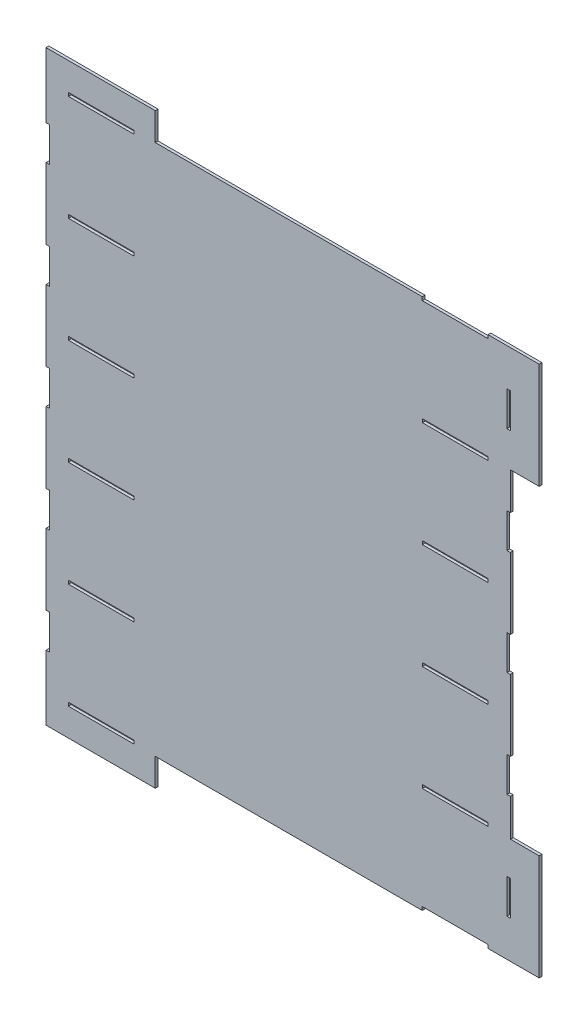
SolidWorks part; units mm, degrees
material "6061-T6 (SS)"
ref_plane "X-Y Datum" through (0, 0, 0) normal (0, 0, 1) x (1, 0, 0)
ref_plane "X-Z Datum" through (0, 0, 0) normal (0, 1, 0) x (1, 0, 0)
ref_plane "Y-Z Datum" through (0, 0, 0) normal (1, 0, 0) x (0, 0, -1)
sketch "Sketch2" plane through (0, 0, 0) normal (0, 0, 1) x (1, 0, 0)
  line L111 (-213.36, -263.2075) -> (-213.36, -269.6845)
  line L123 (-213.36, 244.2845) -> (-213.36, -244.2845)
  line L125 (213.36, 205.7205) -> (213.36, 174.8985)
  line L126 (-213.36, 244.2845) -> (213.36, -244.2845) construction
  line L127 (-213.36, -244.2845) -> (213.36, 244.2845) construction
  line L128 (132.334, -244.2845) -> (192.786, -244.2845)
  line L129 (132.334, -244.2845) -> (132.334, -241.1095)
  line L130 (132.334, -241.1095) -> (192.786, -241.1095)
  line L131 (192.786, -244.2845) -> (192.786, -241.1095)
  line L132 (0, -43.0151) -> (0, 43.0151) construction
  line L136 (55.1739, 0) -> (-55.1739, 0) construction
  line L137 (-213.36, -44.577) -> (213.36, -44.577) construction
  line L138 (-213.36, -134.239) -> (213.36, -134.239) construction
  line L142 (-213.36, 0) -> (213.36, 0) construction
  line L144 (213.36, -194.945) -> (213.36, -163.195)
  line L147 (-217.17, 100.6475) -> (209.55, 100.6475) construction
  line L148 (-217.17, 190.3095) -> (209.55, 190.3095) construction
  line L149 (213.36, 116.0585) -> (210.185, 116.0585) construction
  line L150 (-213.36, -89.662) -> (213.36, -89.662) construction
  line L151 (-213.36, -179.07) -> (213.36, -179.07) construction
  line L152 (213.36, -194.945) -> (210.185, -194.945) construction
  line L154 (210.185, -194.945) -> (210.185, -163.195) construction
  line L155 (-213.36, -194.945) -> (-210.185, -194.945) construction
  line L156 (-210.185, -194.945) -> (-210.185, -163.195) construction
  line L157 (-210.185, -163.195) -> (-213.36, -163.195) construction
  line L158 (-210.185, -73.533) -> (-213.36, -73.533) construction
  line L159 (-210.185, -105.283) -> (-210.185, -73.533) construction
  line L160 (-213.36, -105.283) -> (-210.185, -105.283) construction
  line L161 (210.185, 116.0585) -> (210.185, 85.2365) construction
  line L162 (210.185, 85.2365) -> (213.36, 85.2365) construction
  line L163 (213.36, 26.3965) -> (210.185, 26.3965) construction
  line L164 (-210.185, 16.129) -> (-213.36, 16.129) construction
  line L165 (-210.185, -15.621) -> (-210.185, 16.129) construction
  line L166 (-213.36, -15.621) -> (-210.185, -15.621) construction
  line L167 (210.185, 26.3965) -> (210.185, -4.4255) construction
  line L168 (210.185, -4.4255) -> (213.36, -4.4255) construction
  line L169 (213.36, -63.2655) -> (210.185, -63.2655) construction
  line L170 (-210.185, 105.791) -> (-213.36, 105.791) construction
  line L171 (-210.185, 74.041) -> (-210.185, 105.791) construction
  line L172 (-213.36, 74.041) -> (-210.185, 74.041) construction
  line L173 (210.185, -63.2655) -> (210.185, -94.0875) construction
  line L174 (210.185, -94.0875) -> (213.36, -94.0875) construction
  line L175 (213.36, 244.2845) -> (239.8083, 244.2845)
  line L176 (-210.185, 195.453) -> (-213.36, 195.453) construction
  line L177 (-210.185, 163.703) -> (-210.185, 195.453) construction
  line L178 (-213.36, 163.703) -> (-210.185, 163.703) construction
  line L179 (213.36, 205.7205) -> (210.185, 205.7205) construction
  line L180 (210.185, 205.7205) -> (210.185, 174.8985) construction
  line L181 (210.185, 174.8985) -> (213.36, 174.8985) construction
  line L183 (-213.36, 244.2845) -> (-213.36, 269.6845)
  line L184 (-213.36, 269.6845) -> (-113.03, 269.6845)
  line L185 (-113.03, 269.6845) -> (-113.03, 244.2845)
  line L186 (-113.03, 244.2845) -> (213.36, 244.2845)
  line L189 (-213.36, -244.2845) -> (-213.36, -263.2075)
  line L190 (-213.36, -269.6845) -> (-113.03, -269.6845)
  line L191 (213.36, -244.2845) -> (239.8083, -244.2845)
  line L192 (239.8083, -244.2845) -> (239.8083, -147.0025)
  line L193 (239.8083, -147.0025) -> (213.36, -147.0025)
  line L194 (210.185, -163.195) -> (213.36, -163.195) construction
  line L195 (239.8083, 244.2845) -> (239.8083, 147.0025)
  line L196 (239.8083, 147.0025) -> (213.36, 147.0025)
  line L197 (213.36, 147.0025) -> (213.36, -147.0025)
  line L205 (132.334, -225.2345) -> (192.786, -225.2345) construction
  line L206 (132.334, -225.2345) -> (132.334, -228.4095) construction
  line L207 (132.334, -228.4095) -> (192.786, -228.4095) construction
  line L208 (192.786, -225.2345) -> (192.786, -228.4095) construction
  line L216 (192.786, 225.2345) -> (192.786, 228.4095) construction
  line L217 (132.334, 225.2345) -> (192.786, 225.2345) construction
  line L218 (132.334, 228.4095) -> (192.786, 228.4095) construction
  line L219 (132.334, 225.2345) -> (132.334, 228.4095) construction
  line L220 (132.334, 244.2845) -> (132.334, 241.1095)
  line L221 (192.786, 244.2845) -> (192.786, 241.1095)
  line L222 (132.334, 244.2845) -> (192.786, 244.2845)
  line L223 (132.334, 241.1095) -> (192.786, 241.1095)
  line L224 (-192.786, -244.2845) -> (-192.786, -241.1095)
  line L225 (-192.786, -225.2345) -> (-192.786, -228.4095)
  line L226 (-132.334, -225.2345) -> (-132.334, -228.4095) construction
  line L227 (-132.334, -244.2845) -> (-132.334, -241.1095)
  line L228 (-132.334, -244.2845) -> (-192.786, -244.2845)
  line L229 (-132.334, -241.1095) -> (-192.786, -241.1095)
  line L230 (-132.334, -225.2345) -> (-192.786, -225.2345) construction
  line L231 (-132.334, -228.4095) -> (-192.786, -228.4095) construction
  line L232 (-132.334, 225.2345) -> (-132.334, 228.4095) construction
  line L233 (-192.786, 225.2345) -> (-192.786, 228.4095) construction
  line L234 (-132.334, 225.2345) -> (-192.786, 225.2345) construction
  line L235 (-132.334, 228.4095) -> (-192.786, 228.4095) construction
  line L236 (-192.786, 244.2845) -> (-192.786, 241.1095)
  line L237 (-132.334, 244.2845) -> (-132.334, 241.1095)
  line L238 (-132.334, 241.1095) -> (-192.786, 241.1095)
  line L239 (192.659, -127.889) -> (192.659, -124.714) construction
  line L240 (132.334, -140.589) -> (192.659, -140.589) construction
  line L241 (132.334, -140.589) -> (132.334, -143.764) construction
  line L242 (132.334, -143.764) -> (192.659, -143.764) construction
  line L243 (192.659, -140.589) -> (192.659, -143.764) construction
  line L244 (132.334, -127.889) -> (132.334, -124.714) construction
  line L245 (132.334, -127.889) -> (192.659, -127.889) construction
  line L246 (132.334, -124.714) -> (192.659, -124.714) construction
  line L247 (132.334, -50.927) -> (192.659, -50.927) construction
  line L248 (132.334, -54.102) -> (192.659, -54.102) construction
  line L249 (132.334, -50.927) -> (132.334, -54.102) construction
  line L250 (192.659, -50.927) -> (192.659, -54.102) construction
  line L251 (192.659, -38.227) -> (192.659, -35.052) construction
  line L252 (132.334, -38.227) -> (192.659, -38.227) construction
  line L253 (132.334, -35.052) -> (192.659, -35.052) construction
  line L254 (132.334, -38.227) -> (132.334, -35.052) construction
  line L255 (132.334, 38.735) -> (192.659, 38.735) construction
  line L256 (132.334, 35.56) -> (192.659, 35.56) construction
  line L257 (132.334, 38.735) -> (132.334, 35.56) construction
  line L258 (192.659, 38.735) -> (192.659, 35.56) construction
  line L259 (192.659, 51.435) -> (192.659, 54.61) construction
  line L260 (132.334, 51.435) -> (192.659, 51.435) construction
  line L261 (132.334, 54.61) -> (192.659, 54.61) construction
  line L262 (132.334, 51.435) -> (132.334, 54.61) construction
  line L263 (132.334, 128.397) -> (192.659, 128.397) construction
  line L264 (132.334, 125.222) -> (192.659, 125.222) construction
  line L265 (132.334, 128.397) -> (132.334, 125.222) construction
  line L266 (192.659, 128.397) -> (192.659, 125.222) construction
  line L267 (192.659, 141.097) -> (192.659, 144.272) construction
  line L268 (132.334, 141.097) -> (192.659, 141.097) construction
  line L269 (132.334, 144.272) -> (192.659, 144.272) construction
  line L270 (132.334, 141.097) -> (132.334, 144.272) construction
  line L271 (-192.659, 141.097) -> (-192.659, 144.272) construction
  line L272 (-192.659, 128.397) -> (-192.659, 125.222) construction
  line L273 (-132.334, 128.397) -> (-132.334, 125.222) construction
  line L274 (-132.334, 141.097) -> (-132.334, 144.272) construction
  line L275 (-132.334, 38.735) -> (-132.334, 35.56) construction
  line L276 (-132.334, 51.435) -> (-132.334, 54.61) construction
  line L277 (-192.659, 51.435) -> (-192.659, 54.61) construction
  line L278 (-192.659, 38.735) -> (-192.659, 35.56) construction
  line L279 (-132.334, 35.56) -> (-192.659, 35.56) construction
  line L280 (-132.334, 38.735) -> (-192.659, 38.735) construction
  line L281 (-132.334, 51.435) -> (-192.659, 51.435) construction
  line L282 (-132.334, 54.61) -> (-192.659, 54.61) construction
  line L283 (-132.334, 125.222) -> (-192.659, 125.222) construction
  line L284 (-132.334, 128.397) -> (-192.659, 128.397) construction
  line L285 (-132.334, 141.097) -> (-192.659, 141.097) construction
  line L286 (-132.334, 144.272) -> (-192.659, 144.272) construction
  line L287 (-132.334, -50.927) -> (-132.334, -54.102) construction
  line L288 (-132.334, -54.102) -> (-192.659, -54.102) construction
  line L289 (-132.334, -50.927) -> (-192.659, -50.927) construction
  line L290 (-192.659, -50.927) -> (-192.659, -54.102) construction
  line L291 (-192.659, -38.227) -> (-192.659, -35.052) construction
  line L292 (-132.334, -38.227) -> (-132.334, -35.052) construction
  line L293 (-132.334, -35.052) -> (-192.659, -35.052) construction
  line L294 (-132.334, -38.227) -> (-192.659, -38.227) construction
  line L295 (-132.334, -127.889) -> (-132.334, -124.714) construction
  line L296 (-132.334, -124.714) -> (-192.659, -124.714) construction
  line L297 (-132.334, -127.889) -> (-192.659, -127.889) construction
  line L298 (-192.659, -127.889) -> (-192.659, -124.714) construction
  line L299 (-192.659, -140.589) -> (-192.659, -143.764) construction
  line L300 (-132.334, -140.589) -> (-132.334, -143.764) construction
  line L301 (-132.334, -140.589) -> (-192.659, -140.589) construction
  line L302 (-132.334, -143.764) -> (-192.659, -143.764) construction
  line L303 (-192.786, 244.2845) -> (-132.334, 244.2845)
  line L304 (-113.03, -244.2845) -> (213.36, -244.2845)
  line L305 (-113.03, -269.6845) -> (-113.03, -244.2845)
  line L306 (-213.36, 244.2845) -> (-113.03, 244.2845) construction
  point P4 (0, 0)
  point P9 (162.56, -241.1095)
  point P16 (-213.36, -134.239)
  point P19 (-213.36, -44.577)
  point P26 (-192.786, 231.4575)
  point P28 (50.165, 244.2845)
  point P33 (0, 0)
  point P34 (0, 0)
  point P71 (213.36, 174.8985)
  point P72 (213.36, 205.7205)
  dimension "D1" = 426.72
  dimension "D2" = 488.569
  dimension "D3" = 60.452
  dimension "D4" = 3.175
  dimension "D5" = 50.8
  dimension "D6" = 2
  dimension "D7" = 0
  dimension "D9" = 15.875
  dimension "D10" = 15.875
  dimension "D11" = 5
  dimension "D12" = 100.33
  dimension "D13" = 25.4
  dimension "D14" = 97.282
  dimension "D15" = 3.175
  dimension "D16" = 53.975
  dimension "D17" = 15.875
  dimension "D18" = 15.875
  dimension "D19" = 3.175
  dimension "D21" = 3.175
  dimension "D22" = 19.05
  dimension "D24" = 89.408
  dimension "D25" = 28.956
  dimension "D26" = 28.956
  dimension "D27" = 3.175
  dimension "D28" = 60.325
  dimension "D29" = 9.525
  dimension "D30" = 4
  dimension "D31" = 9.525
  dimension "D32" = 70.612
  dimension "D8" = 2
  dimension "D20" = 4
extrude "Boss-Extrude3" add sketch "Sketch2" along normal blind 2.54 separate body
sketch "Sketch3" plane through (0, 0, 2.54) normal (0, 0, 1) x (1, 0, 0)
  line L0 (-213.36, 0) -> (213.36, 0) construction
  line L6 (-192.659, -1.5875) -> (-132.334, -1.5875)
  line L7 (-213.36, 269.6845) -> (-213.36, -269.6845) construction
  line L8 (-132.334, -1.5875) -> (-132.334, 0)
  line L9 (-132.334, 0) -> (-132.334, 1.5875)
  line L10 (213.36, 147.0025) -> (213.36, -147.0025) construction
  line L11 (-132.334, 1.5875) -> (-192.659, 1.5875)
  line L12 (-192.659, 1.5875) -> (-192.659, -134.239)
  line L13 (-213.36, 0) -> (239.8083, 0) construction
  line L16 (-213.36, 269.6845) -> (-213.36, -269.6845) construction
  line L17 (0, -43.0151) -> (0, 43.0151) construction
  line L18 (239.8083, -244.2845) -> (239.8083, -147.0025) construction
  line L19 (-213.36, 0) -> (239.8083, 0) construction
  line L20 (-213.36, 269.6845) -> (-213.36, -269.6845) construction
  line L21 (-213.36, 0) -> (213.36, 0) construction
  line L22 (-213.36, 269.6845) -> (-213.36, -269.6845) construction
  line L23 (213.36, 147.0025) -> (213.36, -147.0025) construction
  line L24 (239.8083, 244.2845) -> (239.8083, 147.0025) construction
  line L26 (192.659, -134.239) -> (192.659, -1.5875)
  line L27 (192.659, 1.5875) -> (192.659, -134.239)
  line L28 (132.334, 0) -> (132.334, 1.5875)
  line L29 (132.334, -1.5875) -> (132.334, 0)
  line L30 (132.334, 1.5875) -> (192.659, 1.5875)
  line L31 (192.659, -1.5875) -> (132.334, -1.5875)
  line L32 (132.334, 91.2495) -> (192.659, 91.2495)
  line L33 (192.659, 88.0745) -> (132.334, 88.0745)
  line L34 (192.659, 91.2495) -> (192.659, -44.577)
  line L35 (192.659, -44.577) -> (192.659, 88.0745)
  line L36 (132.334, 89.662) -> (132.334, 91.2495)
  line L37 (132.334, 88.0745) -> (132.334, 89.662)
  line L38 (-192.659, 88.0745) -> (-132.334, 88.0745)
  line L39 (-132.334, 88.0745) -> (-132.334, 89.662)
  line L40 (-132.334, 89.662) -> (-132.334, 91.2495)
  line L41 (-132.334, 91.2495) -> (-192.659, 91.2495)
  line L42 (-192.659, -44.577) -> (-192.659, 88.0745)
  line L43 (-192.659, 91.2495) -> (-192.659, -44.577)
  line L44 (132.334, 180.9115) -> (192.659, 180.9115)
  line L45 (192.659, 177.7365) -> (132.334, 177.7365)
  line L46 (192.659, 180.9115) -> (192.659, 45.085)
  line L47 (192.659, 45.085) -> (192.659, 177.7365)
  line L48 (132.334, 179.324) -> (132.334, 180.9115)
  line L49 (132.334, 177.7365) -> (132.334, 179.324)
  line L50 (-192.659, 177.7365) -> (-132.334, 177.7365)
  line L51 (-132.334, 177.7365) -> (-132.334, 179.324)
  line L52 (-132.334, 179.324) -> (-132.334, 180.9115)
  line L53 (-132.334, 180.9115) -> (-192.659, 180.9115)
  line L54 (-192.659, 45.085) -> (-192.659, 177.7365)
  line L55 (-192.659, 180.9115) -> (-192.659, 45.085)
  line L56 (132.334, 270.5735) -> (192.659, 270.5735)
  line L57 (192.659, 267.3985) -> (132.334, 267.3985)
  line L58 (192.659, 270.5735) -> (192.659, 134.747)
  line L59 (192.659, 134.747) -> (192.659, 267.3985)
  line L60 (132.334, 268.986) -> (132.334, 270.5735)
  line L61 (132.334, 267.3985) -> (132.334, 268.986)
  line L62 (-192.659, 267.3985) -> (-132.334, 267.3985)
  line L63 (-132.334, 267.3985) -> (-132.334, 268.986)
  line L64 (-132.334, 268.986) -> (-132.334, 270.5735)
  line L65 (-132.334, 270.5735) -> (-192.659, 270.5735)
  line L66 (-192.659, 134.747) -> (-192.659, 267.3985)
  line L67 (-192.659, 270.5735) -> (-192.659, 134.747)
  line L68 (-192.659, -134.239) -> (-192.659, -1.5875)
  dimension "D1" = 3.175
  dimension "D2" = 60.325
  dimension "D3" = 0
  dimension "D4" = 4
extrude "Cut-Extrude1" [suppressed] cut sketch "Sketch3" against normal through all both and the other way through all
sketch "Sketch4" plane through (0, 0, 2.54) normal (0, 0, 1) x (1, 0, 0)
  line L0 (-132.334, -241.1095) -> (-192.786, -241.1095) construction
  line L1 (-192.786, -147.1295) -> (-132.461, -147.1295)
  line L2 (-192.786, -147.1295) -> (-192.786, -143.9545)
  line L3 (-192.786, -143.9545) -> (-132.461, -143.9545)
  line L4 (-132.461, -147.1295) -> (-132.461, -143.9545)
  line L5 (-192.786, -46.8842) -> (-132.461, -46.8842)
  line L6 (-192.786, -50.0592) -> (-132.461, -50.0592)
  line L7 (-132.461, -50.0592) -> (-132.461, -46.8842)
  line L8 (-192.786, -50.0592) -> (-192.786, -46.8842)
  line L9 (-192.786, 50.1862) -> (-132.461, 50.1862)
  line L10 (-192.786, 47.0112) -> (-132.461, 47.0112)
  line L11 (-132.461, 47.0112) -> (-132.461, 50.1862)
  line L12 (-192.786, 47.0112) -> (-192.786, 50.1862)
  line L13 (-192.786, 147.2565) -> (-132.461, 147.2565)
  line L14 (-192.786, 144.0815) -> (-132.461, 144.0815)
  line L15 (-132.461, 144.0815) -> (-132.461, 147.2565)
  line L16 (-192.786, 144.0815) -> (-192.786, 147.2565)
  line L17 (0, -43.0151) -> (0, 43.0151) construction
  line L18 (132.461, -147.1295) -> (132.461, -143.9545)
  line L19 (192.786, -147.1295) -> (192.786, -143.9545)
  line L20 (192.786, -143.9545) -> (132.461, -143.9545)
  line L21 (192.786, -147.1295) -> (132.461, -147.1295)
  line L22 (192.786, -50.0592) -> (192.786, -46.8842)
  line L23 (132.461, -50.0592) -> (132.461, -46.8842)
  line L24 (192.786, -46.8842) -> (132.461, -46.8842)
  line L25 (192.786, -50.0592) -> (132.461, -50.0592)
  line L26 (132.461, 47.0112) -> (132.461, 50.1862)
  line L27 (192.786, 47.0112) -> (192.786, 50.1862)
  line L28 (192.786, 47.0112) -> (132.461, 47.0112)
  line L29 (192.786, 50.1862) -> (132.461, 50.1862)
  line L30 (132.461, 144.0815) -> (132.461, 147.2565)
  line L31 (192.786, 144.0815) -> (192.786, 147.2565)
  line L32 (192.786, 144.0815) -> (132.461, 144.0815)
  line L33 (192.786, 147.2565) -> (132.461, 147.2565)
  line L34 (213.36, -96.9857) -> (-213.36, -96.9857) construction
  line L35 (-213.36, -269.6845) -> (-213.36, 269.6845) construction
  line L36 (-213.36, -194.056) -> (239.8083, -194.056) construction
  line L37 (-192.786, 244.2845) -> (-132.334, 244.2845) construction
  line L38 (-213.36, 0) -> (213.36, 0) construction
  line L39 (-213.36, 194.183) -> (239.8083, 194.183) construction
  line L40 (213.36, 147.0025) -> (213.36, -147.0025) construction
  line L41 (239.8083, -244.2845) -> (239.8083, -147.0025) construction
  line L42 (-213.36, 97.155) -> (213.36, 97.155) construction
  line L43 (239.8083, 244.2845) -> (239.8083, 147.0025) construction
  line L44 (-132.334, 241.1095) -> (-192.786, 241.1095) construction
  line L45 (213.36, -147.0025) -> (213.36, -244.2845) construction
  line L46 (192.786, -244.2845) -> (239.8083, -244.2845) construction
  line L47 (213.36, -209.931) -> (213.36, -178.181)
  line L48 (213.36, -178.181) -> (210.185, -178.181)
  line L49 (210.185, -178.181) -> (210.185, -209.931)
  line L50 (210.185, -209.931) -> (213.36, -209.931)
  line L51 (213.36, -81.153) -> (210.185, -81.153)
  line L52 (210.185, -81.153) -> (210.185, -112.903)
  line L53 (213.36, -112.903) -> (213.36, -81.153)
  line L54 (210.185, -112.903) -> (213.36, -112.903)
  line L55 (213.36, 15.875) -> (210.185, 15.875)
  line L56 (210.185, 15.875) -> (210.185, -15.875)
  line L57 (213.36, -15.875) -> (213.36, 15.875)
  line L58 (210.185, -15.875) -> (213.36, -15.875)
  line L59 (213.36, 112.903) -> (210.185, 112.903)
  line L60 (210.185, 112.903) -> (210.185, 81.153)
  line L61 (213.36, 81.153) -> (213.36, 112.903)
  line L62 (210.185, 81.153) -> (213.36, 81.153)
  line L63 (213.36, 209.931) -> (210.185, 209.931)
  line L64 (210.185, 209.931) -> (210.185, 178.181)
  line L65 (213.36, 178.181) -> (213.36, 209.931)
  line L66 (210.185, 178.181) -> (213.36, 178.181)
  line L67 (-210.185, -112.903) -> (-213.36, -112.903)
  line L68 (-213.36, -81.153) -> (-210.185, -81.153)
  line L69 (-210.185, -81.153) -> (-210.185, -112.903)
  line L70 (-213.36, -112.903) -> (-213.36, -81.153)
  line L71 (-210.185, -15.875) -> (-213.36, -15.875)
  line L72 (-210.185, 15.875) -> (-210.185, -15.875)
  line L73 (-213.36, -15.875) -> (-213.36, 15.875)
  line L74 (-213.36, 15.875) -> (-210.185, 15.875)
  line L75 (-210.185, -209.931) -> (-213.36, -209.931)
  line L76 (-213.36, -209.931) -> (-213.36, -178.181)
  line L77 (-210.185, -178.181) -> (-210.185, -209.931)
  line L78 (-213.36, -178.181) -> (-210.185, -178.181)
  line L79 (-210.185, 81.153) -> (-213.36, 81.153)
  line L80 (-210.185, 112.903) -> (-210.185, 81.153)
  line L81 (-213.36, 81.153) -> (-213.36, 112.903)
  line L82 (-213.36, 112.903) -> (-210.185, 112.903)
  line L83 (-210.185, 178.181) -> (-213.36, 178.181)
  line L84 (-213.36, 178.181) -> (-213.36, 209.931)
  line L85 (-210.185, 209.931) -> (-210.185, 178.181)
  line L86 (-213.36, 209.931) -> (-210.185, 209.931)
  point P43 (0, 0)
  dimension "D1" = 60.325
  dimension "D2" = 3.175
  dimension "D3" = 93.98
  dimension "D5" = 100.33
  dimension "D6" = 97.028
  dimension "D7" = 46.8842
  dimension "D8" = 47.0112
  dimension "D9" = 46.9265
  dimension "D10" = 46.9265
  dimension "D11" = 46.9265
  dimension "D12" = 46.9265
  dimension "D13" = 46.9265
  dimension "D14" = 3.175
  dimension "D15" = 15.875
  dimension "D16" = 31.75
  dimension "D17" = 5
  dimension "D18" = 50.2285
  dimension "D4" = 4
extrude "Cut-Extrude2" cut sketch "Sketch4" against normal through all both and the other way through all
